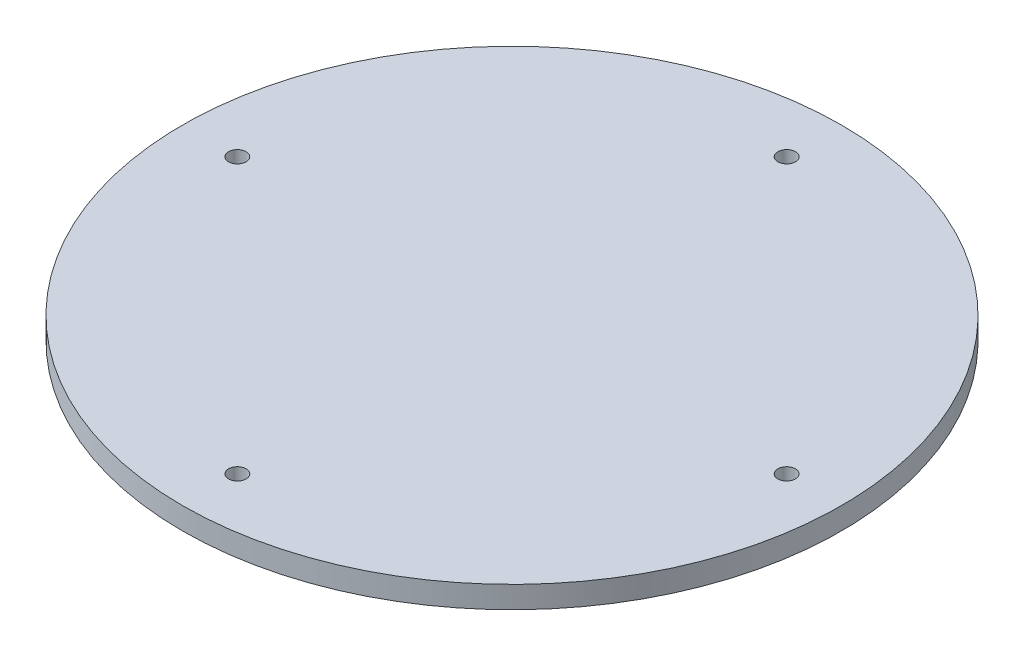
SolidWorks part; units mm, degrees
material "E-Glass Fiber"
ref_plane "Front Plane" through (0, 0, 0) normal (0, 0, 1) x (1, 0, 0)
ref_plane "Top Plane" through (0, 0, 0) normal (0, 1, 0) x (1, 0, 0)
ref_plane "Right Plane" through (0, 0, 0) normal (1, 0, 0) x (0, 0, -1)
sketch "Sketch1" plane through (0, 0, 0) normal (0, 1, 0) x (1, 0, 0)
  line L0 (0, 0) -> (0, 62.5) construction
  circle A1 centre (0, 0) radius 75
  circle A2 centre (0, 62.5) radius 2
  circle A3 centre (62.5, 0) radius 2
  circle A4 centre (0, -62.5) radius 2
  circle A5 centre (-62.5, 0) radius 2
  point P14 (0, 0)
  dimension "D1" = 150
  dimension "D2" = 4
  dimension "D3" = 62.5
  dimension "D4" = 4
extrude "Boss-Extrude1" add sketch "Sketch1" along normal blind 5
sketch "Sketch2" plane through (0, 5, 0) normal (0, 1, 0) x (1, 0, 0)
  line L1 (-53.033, 53.033) -> (53.033, 53.033)
  line L2 (-53.033, 53.033) -> (-53.033, -53.033)
  line L3 (-53.033, -53.033) -> (53.033, -53.033)
  line L4 (53.033, 53.033) -> (53.033, -53.033)
  circle A0 centre (0, 0) radius 75 construction
  point P6 (0, 0)
